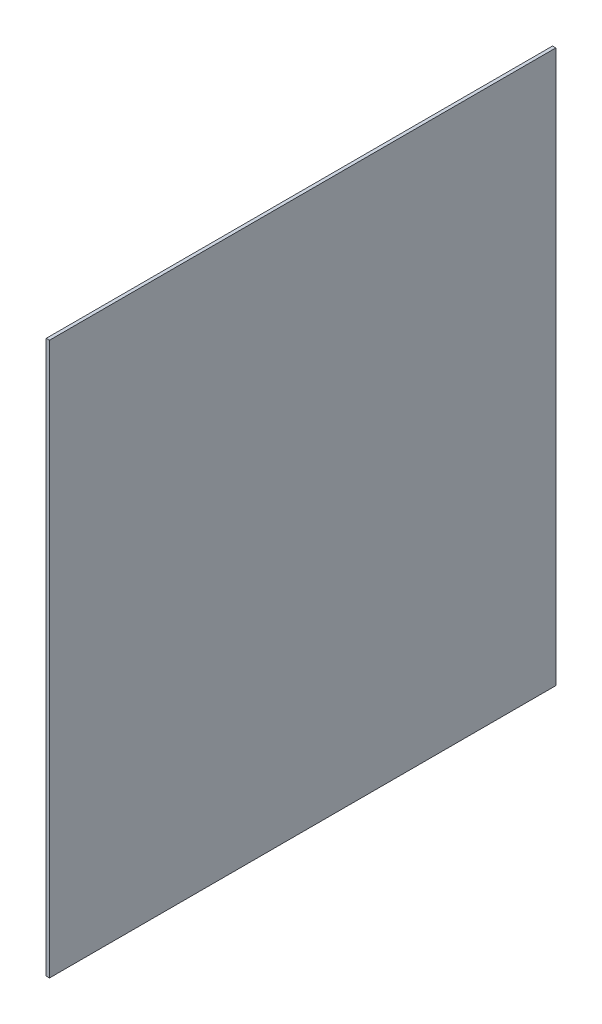
SolidWorks part; units mm, degrees
ref_plane "Front Plane" through (0, 0, 0) normal (0, 0, 1) x (1, 0, 0)
ref_plane "Top Plane" through (0, 0, 0) normal (0, 1, 0) x (1, 0, 0)
ref_plane "Right Plane" through (0, 0, 0) normal (1, 0, 0) x (0, 0, -1)
sketch "Sketch1" plane through (0, 0, 0) normal (1, 0, 0) x (0, 0, -1)
  line L1 (0, 0) -> (1955.8, 0)
  line L2 (0, 0) -> (0, 2133.6)
  line L3 (0, 2133.6) -> (1955.8, 2133.6)
  line L4 (1955.8, 0) -> (1955.8, 2133.6)
  dimension "D1" = 1955.8
  dimension "D2" = 2133.6
extrude "Boss-Extrude1" add sketch "Sketch1" along normal blind 12.7
